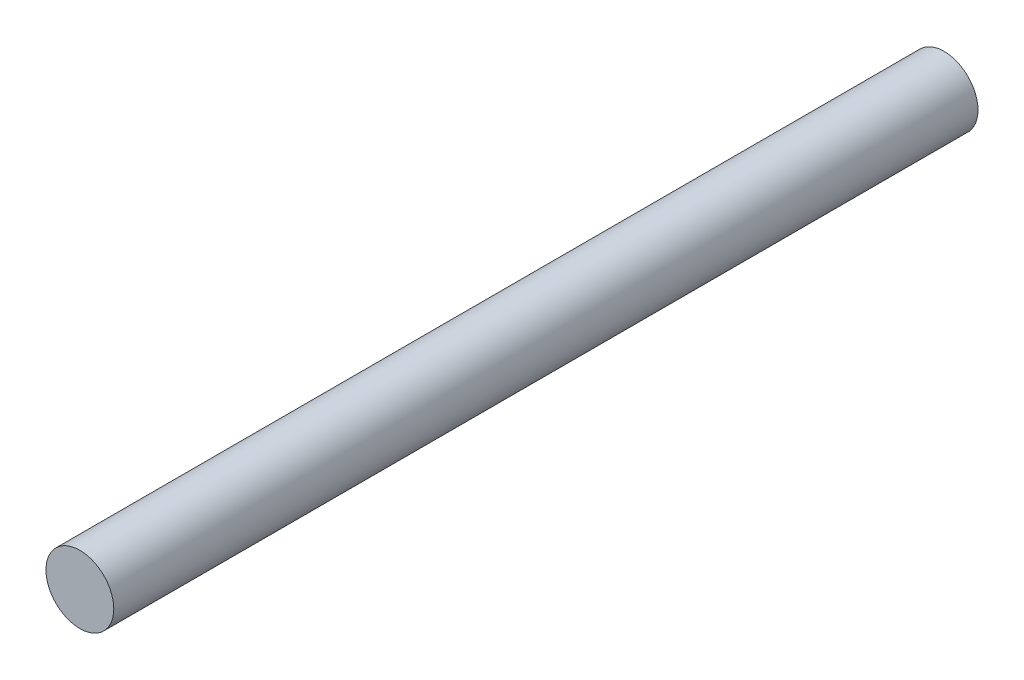
SolidWorks part; units mm, degrees
ref_plane "Front Plane" through (0, 0, 0) normal (0, 0, 1) x (1, 0, 0)
ref_plane "Top Plane" through (0, 0, 0) normal (0, 1, 0) x (1, 0, 0)
ref_plane "Right Plane" through (0, 0, 0) normal (1, 0, 0) x (0, 0, -1)
ref_plane "Plane1"
sketch "Sketch1" plane through (0, 0, 0) normal (0, 0, 1) x (1, 0, 0)
  circle A0 centre (0, 0) radius 1.9939
  dimension "D1" = 3.9878
extrude "Axle" add sketch "Sketch1" along normal blind 25.4 and the other way blind 25.4
